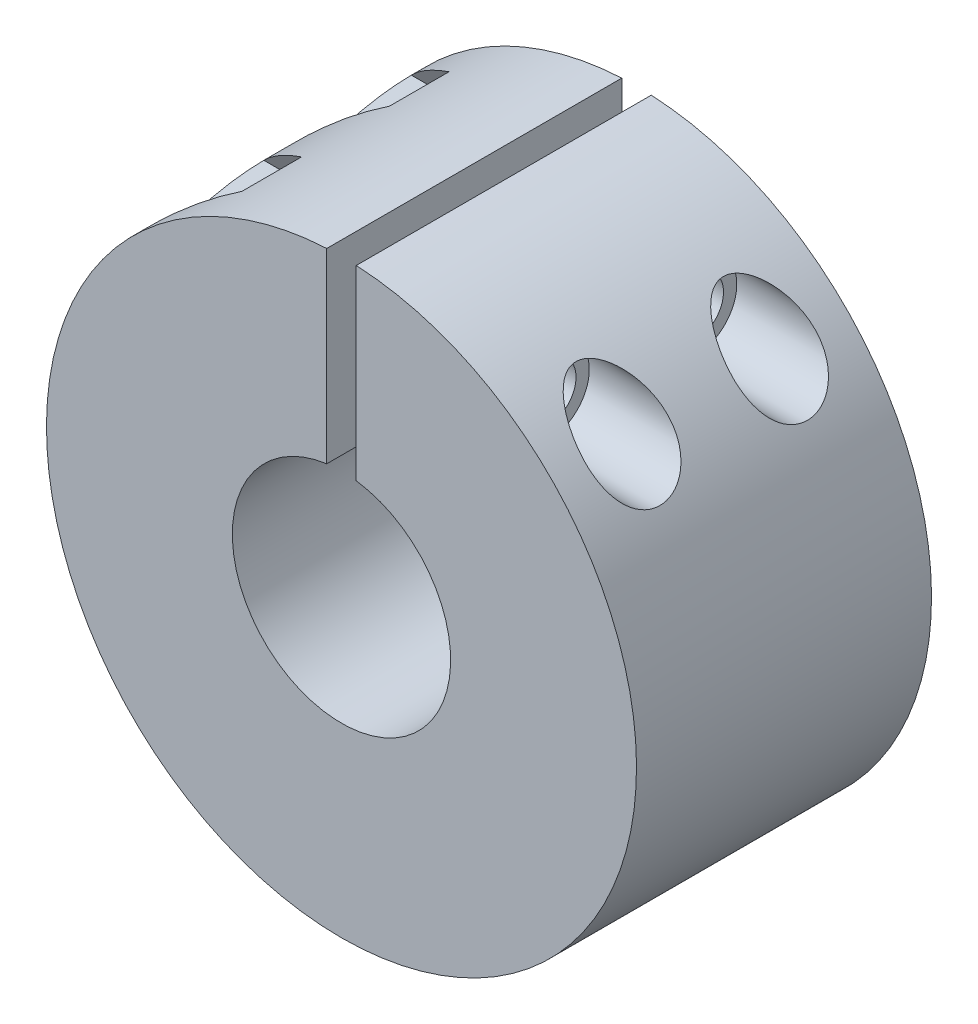
SolidWorks part; units mm, degrees
ref_plane "Front Plane" through (0, 0, 0) normal (0, 0, 1) x (1, 0, 0)
ref_plane "Top Plane" through (0, 0, 0) normal (0, 1, 0) x (1, 0, 0)
ref_plane "Right Plane" through (0, 0, 0) normal (1, 0, 0) x (0, 0, -1)
sketch "Sketch1" plane through (0, 0, 0) normal (0, 0, 1) x (1, 0, 0)
  circle A0 centre (0, 0) radius 25.4
  dimension "D1" = 50.8
extrude "Boss-Extrude1" add sketch "Sketch1" along normal blind 25.4
sketch "Sketch2" plane through (0, 0, 0) normal (0, 0, -1) x (-1, 0, 0)
  circle A0 centre (0, 0) radius 4.8895
  dimension "D1" = 9.779
extrude "Cut-Extrude1" cut sketch "Sketch2" against normal blind 11.43 contours A0
sketch "Sketch3" plane through (0, 0, 25.4) normal (0, 0, 1) x (1, 0, 0)
  circle A0 centre (0, 0) radius 9.398
  dimension "D1" = 18.796
extrude "Cut-Extrude2" cut sketch "Sketch3" against normal up to surface (13.97 mm away) contours A0 up to face at (-4.8895, 0, 11.43)
sketch "Centerline" plane through (0, 0, 0) normal (0, 0, -1) x (-1, 0, 0)
  line L0 (0, 0) -> (0, 25.4) construction
  circle A0 centre (0, 0) radius 25.4 construction
  circle A1 centre (0, 0) radius 25.4 construction
sketch "Sketch7" plane through (0, 0, 0) normal (0, 0, -1) x (-1, 0, 0)
  line L0 (0, 0) -> (0, 25.4) construction
  line L1 (-1.27, 0) -> (1.27, 0)
  line L2 (-1.27, 0) -> (-1.27, 25.4)
  line L3 (-1.27, 25.4) -> (1.27, 25.4)
  line L4 (1.27, 0) -> (1.27, 25.4)
  line L5 (-1.27, 0) -> (1.27, 25.4) construction
  line L6 (-1.27, 25.4) -> (1.27, 0) construction
  point P0 (0, 12.7)
  dimension "D1" = 25.4
  dimension "D2" = 2.54
extrude "Divide" cut sketch "Sketch7" against normal up to next
sketch "Sketch8" plane through (1.27, 0, 0) normal (-1, 0, 0) x (0, 0, 1)
  line L0 (25.4, 25.3682) -> (25.4, 9.3118) construction
  line L1 (25.4, 25.3682) -> (0, 25.3682) construction
  circle A0 centre (19.05, 17.7482) radius 2.413
  dimension "D1" = 4.826
  dimension "D2" = 6.35
  dimension "D3" = 7.62
extrude "4-40 through hole" cut sketch "Sketch8" against normal through all both and the other way through all
sketch3d "head plane" plane through (0, 0, 0) normal (0, 0, 1) x (1, 0, 0)
  dimension "D1" = 10.16
sketch "Sketch9" plane through (11.43, 0, 0) normal (-1, 0, 0) x (0, 0, 1)
  circle A0 centre (19.05, 17.7482) radius 3.556
  dimension "D1" = 7.112
extrude "4-40 head clearance" cut sketch "Sketch9" against normal through all contours A0
sketch3d "nut plane" plane through (0, 0, 0) normal (0, 0, 1) x (1, 0, 0)
  dimension "D1" = 10.16
sketch "Sketch10" plane through (-11.43, 0, 0) normal (1, 0, 0) x (0, 0, -1)
  line L0 (0, 25.3682) -> (-25.4, 25.3682) construction
  line L1 (-21.6163, 13.3032) -> (-16.4837, 13.3032)
  line L2 (-16.4837, 13.3032) -> (-13.9174, 17.7482)
  line L3 (-13.9174, 17.7482) -> (-16.4837, 22.1932)
  line L4 (-16.4837, 22.1932) -> (-21.6163, 22.1932)
  line L5 (-21.6163, 22.1932) -> (-24.1826, 17.7482)
  line L6 (-24.1826, 17.7482) -> (-21.6163, 13.3032)
  circle A0 centre (-19.05, 17.7482) radius 4.445 construction
  dimension "D1" = 8.89
extrude "4-40 hex nut depression" cut sketch "Sketch10" against normal through all contours L3 L4 L5 L6 L1 L2
pattern_linear "LPattern1" count 2 spacing 12.7 along (0, 0, -1) of "4-40 hex nut depression", "4-40 through hole", "4-40 head clearance"
